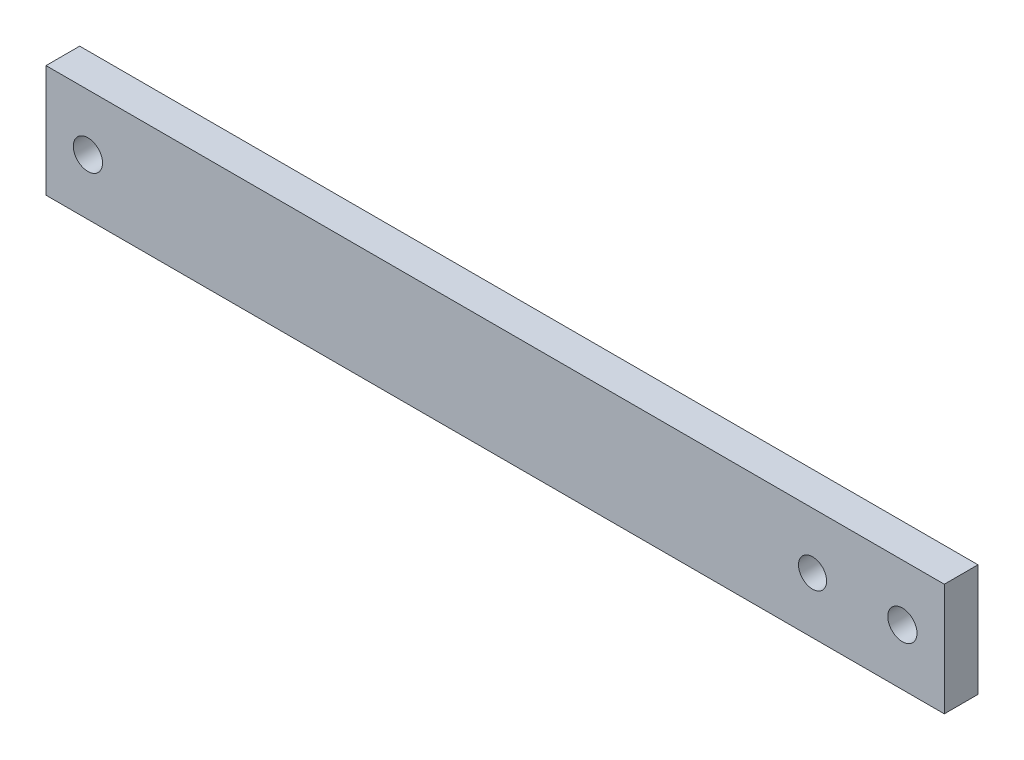
SolidWorks part; units mm, degrees
ref_plane "Front Plane" through (0, 0, 0) normal (0, 0, 1) x (1, 0, 0)
ref_plane "Top Plane" through (0, 0, 0) normal (0, 1, 0) x (1, 0, 0)
ref_plane "Right Plane" through (0, 0, 0) normal (1, 0, 0) x (0, 0, -1)
sketch "Sketch1" plane through (0, 0, 0) normal (0, 0, 1) x (1, 0, 0)
  line L0 (30, 0) -> (40, 0) construction
  line L1 (31.2664, 0) -> (111.2664, 0)
  line L2 (31.2664, 0) -> (31.2664, 10)
  line L3 (31.2664, 10) -> (111.2664, 10)
  line L4 (111.2664, 0) -> (111.2664, 10)
  line L5 (71.2664, 10) -> (71.2664, 0) construction
  circle A0 centre (35, 5) radius 1.301
  circle A1 centre (107.5328, 5) radius 1.301
  dimension "D1" = 80
  dimension "D2" = 10
extrude "Boss-Extrude1" add sketch "Sketch1" along normal blind 3
hole_wizard "M3 Tapped Hole1" positions "Sketch3" profile "Sketch2" tap size "M3" standard "ISO"
sketch "Sketch3" plane through (0, 0, 3) normal (0, 0, 1) x (1, 0, 0)
  point P0 (99.5328, 5)
sketch "Sketch2" plane through (99.5328, 5, 3) normal (1, 0, 0) x (0, -1, 0)
  line L0 (0, 0) -> (0, 8.2511)
  line L1 (0, 8.2511) -> (1.25, 7.5)
  line L2 (1.25, 7.5) -> (1.25, 0)
  line L5 (1.25, 0) -> (0, 0)
  line L10 (0, 8.2511) -> (-1.25, 7.5) construction
  line L11 (0, -6.35) -> (0, 107.95) construction
  dimension "Tap Drill Dia." = 2.5
  dimension "Tap Drill Depth" = 7.5
  dimension "Drill Angle" = 118
cosmetic thread "Hole Thread1"
